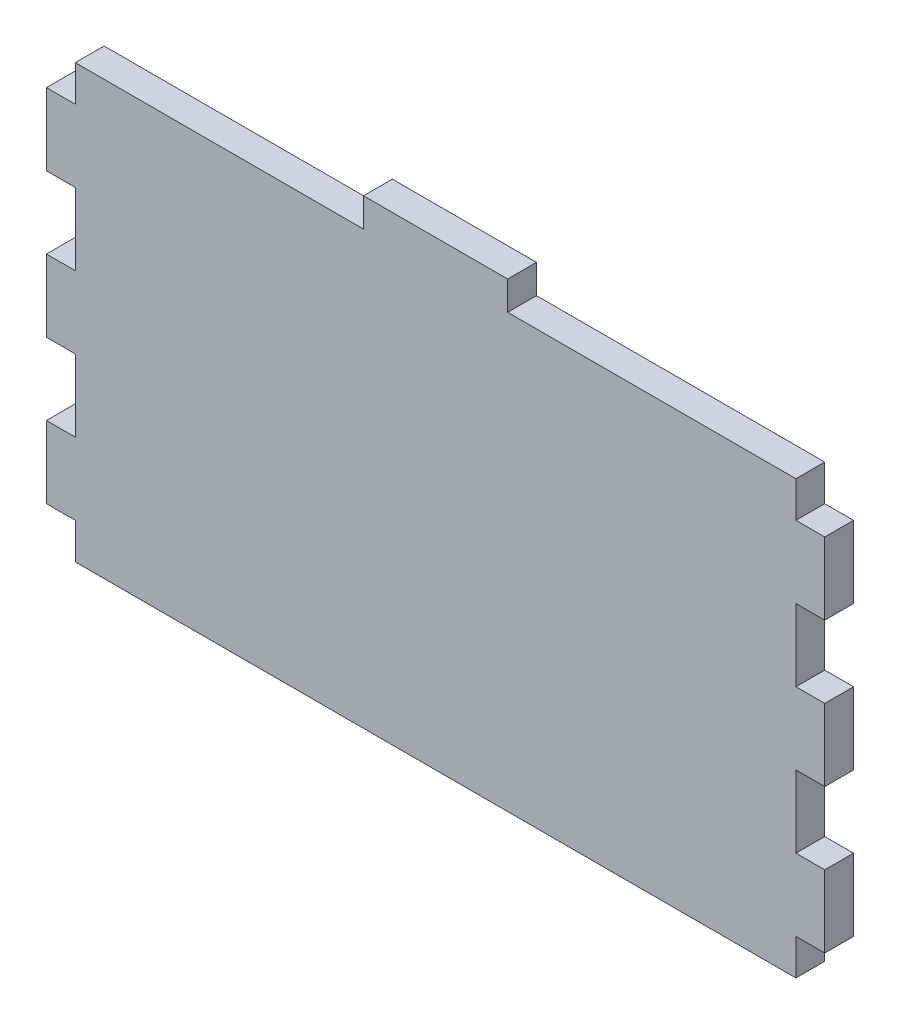
SolidWorks part; units mm, degrees
ref_plane "Front Plane" through (0, 0, 0) normal (0, 0, 1) x (1, 0, 0)
ref_plane "Top Plane" through (0, 0, 0) normal (0, 1, 0) x (1, 0, 0)
ref_plane "Right Plane" through (0, 0, 0) normal (1, 0, 0) x (0, 0, -1)
sketch "Sketch1" plane through (0, 0, 0) normal (0, 0, 1) x (1, 0, 0)
  line L0 (-50, 30) -> (-30, 30)
  line L1 (-50, -30) -> (50, -30)
  line L2 (-50, -30) -> (-50, 30)
  line L3 (-50, 30) -> (50, 30)
  line L4 (50, -30) -> (50, 30)
  line L5 (0, 30) -> (0, -30) construction
  line L6 (-50, 0) -> (50, 0) construction
  line L7 (-30, 30) -> (-10, 30)
  line L8 (-10, 30) -> (10, 30)
  line L9 (10, 30) -> (30, 30)
  line L10 (50, -30) -> (50, -10)
  line L11 (50, -10) -> (50, 10)
  line L12 (-50, -30) -> (-50, -10)
  line L13 (-45, 26) -> (-35, 26)
  line L14 (-45, 26) -> (-45, 34)
  line L15 (-45, 34) -> (-35, 34)
  line L16 (-35, 26) -> (-35, 34)
  line L17 (-40, 34) -> (-40, 26) construction
  line L18 (-45, 30) -> (-35, 30) construction
  line L19 (-25, 26) -> (-15, 26)
  line L20 (-25, 26) -> (-25, 34)
  line L21 (-25, 34) -> (-15, 34)
  line L22 (-15, 26) -> (-15, 34)
  line L23 (-20, 34) -> (-20, 26) construction
  line L24 (-25, 30) -> (-15, 30) construction
  line L25 (-5, 26) -> (5, 26)
  line L26 (-5, 26) -> (-5, 34)
  line L27 (-5, 34) -> (5, 34)
  line L28 (5, 26) -> (5, 34)
  line L29 (0, 34) -> (0, 26) construction
  line L30 (-5, 30) -> (5, 30) construction
  line L31 (15, 26) -> (25, 26)
  line L32 (15, 26) -> (15, 34)
  line L33 (15, 34) -> (25, 34)
  line L34 (25, 26) -> (25, 34)
  line L35 (20, 34) -> (20, 26) construction
  line L36 (15, 30) -> (25, 30) construction
  line L37 (35, 26) -> (45, 26)
  line L38 (35, 26) -> (35, 34)
  line L39 (35, 34) -> (45, 34)
  line L40 (45, 26) -> (45, 34)
  line L41 (40, 34) -> (40, 26) construction
  line L42 (35, 30) -> (45, 30) construction
  line L43 (46, 25) -> (54, 25)
  line L44 (46, 25) -> (46, 15)
  line L45 (46, 15) -> (54, 15)
  line L46 (54, 25) -> (54, 15)
  line L47 (50, 15) -> (50, 25) construction
  line L48 (46, 20) -> (54, 20) construction
  line L49 (46, 5) -> (54, 5)
  line L50 (46, 5) -> (46, -5)
  line L51 (46, -5) -> (54, -5)
  line L52 (54, 5) -> (54, -5)
  line L53 (50, -5) -> (50, 5) construction
  line L54 (46, 0) -> (54, 0) construction
  line L55 (46, -15) -> (54, -15)
  line L56 (46, -15) -> (46, -25)
  line L57 (46, -25) -> (54, -25)
  line L58 (54, -15) -> (54, -25)
  line L59 (50, -25) -> (50, -15) construction
  line L60 (46, -20) -> (54, -20) construction
  line L61 (-50, -10) -> (-50, 10)
  line L63 (-54, 25) -> (-46, 25)
  line L64 (-54, 25) -> (-54, 15)
  line L65 (-54, 15) -> (-46, 15)
  line L66 (-46, 25) -> (-46, 15)
  line L67 (-50, 15) -> (-50, 25) construction
  line L68 (-54, 20) -> (-46, 20) construction
  line L69 (-54, 5) -> (-46, 5)
  line L70 (-54, 5) -> (-54, -5)
  line L71 (-54, -5) -> (-46, -5)
  line L72 (-46, 5) -> (-46, -5)
  line L73 (-50, -5) -> (-50, 5) construction
  line L74 (-54, 0) -> (-46, 0) construction
  line L75 (-54, -15) -> (-46, -15)
  line L76 (-54, -15) -> (-54, -25)
  line L77 (-54, -25) -> (-46, -25)
  line L78 (-46, -15) -> (-46, -25)
  line L79 (-50, -25) -> (-50, -15) construction
  line L80 (-54, -20) -> (-46, -20) construction
  point P0 (0, 0)
  point P4 (-40, 30)
  point P11 (-20, 30)
  point P12 (20, 30)
  point P13 (0, 30)
  point P14 (40, 30)
  point P15 (50, 20)
  point P16 (50, -20)
  point P17 (50, 0)
  point P18 (-40, 30)
  point P22 (-20, 30)
  point P29 (20, 30)
  point P33 (40, 30)
  point P37 (50, 20)
  point P44 (50, -20)
  point P48 (-50, -20)
  point P51 (-50, 0)
  point P52 (-50, 20)
  point P53 (-50, 20)
  point P65 (-50, -20)
  dimension "D1" = 60
  dimension "D2" = 100
  dimension "D3" = 20
  dimension "D4" = 20
  dimension "D5" = 20
  dimension "D6" = 20
  dimension "D7" = 20
  dimension "D8" = 20
  dimension "D9" = 20
  dimension "D10" = 20
  dimension "D11" = 10
  dimension "D12" = 10
  dimension "D13" = 10
  dimension "D14" = 10
  dimension "D15" = 10
  dimension "D16" = 10
  dimension "D17" = 10
  dimension "D18" = 10
  dimension "D19" = 20
  dimension "D20" = 10
  dimension "D21" = 20
  dimension "D22" = 10
  dimension "D23" = 20
  dimension "D24" = 10
  dimension "D25" = 8
  dimension "D26" = 8
  dimension "D27" = 8
  dimension "D28" = 8
  dimension "D29" = 8
  dimension "D30" = 8
  dimension "D31" = 8
  dimension "D32" = 8
  dimension "D33" = 8
  dimension "D34" = 8
  dimension "D35" = 8
  dimension "D36" = 10
  dimension "D37" = 10
  dimension "D38" = 10
  dimension "D39" = 10
  dimension "D40" = 10
  dimension "D41" = 10
  dimension "D42" = 10
  dimension "D43" = 10
  dimension "D44" = 10
  dimension "D45" = 10
  dimension "D46" = 10
extrude "Boss-Extrude1" add sketch "Sketch1" along normal blind 4 contours L75 L78 L77 L2 L1 L4 L57 L56 L55 L10 L51 L50 L49 L11 L45 L44 L43 L3 L40 L37 L38 L34 L31 L32 L28 L25 L26 L22 L19 L20 L0 L16 L13 L14 L63 L66 L65 L61 | L64 L65 L2 L63 | L66 L63 L2 L65 | L70 L71 L61 L69 | L72 L69 L61 L71 | L13 L16 L3 L14 | L78 L75 L12 L77 | L76 L77 L12 L75 | L19 L22 L7 L20 | L25 L28 L8 L26 | L31 L34 L9 L32 | L37 L40 L3 L38 | L46 L43 L4 L45 | L44 L45 L4 L43 | L52 L49 L11 L51 | L50 L51 L11 L49 | L56 L57 L10 L55 | L58 L55 L10 L57
sketch "Sketch2" plane through (0, 0, 4) normal (0, 0, 1) x (1, 0, 0)
  line L0 (-50, 30) -> (50, 30) construction
  line L1 (-10, 26) -> (10, 26)
  line L2 (-10, 26) -> (-10, 34)
  line L3 (-10, 34) -> (10, 34)
  line L4 (10, 26) -> (10, 34)
  line L5 (0, 34) -> (0, 26) construction
  line L6 (-10, 30) -> (10, 30) construction
  point P0 (0, 30)
  dimension "D1" = 8
  dimension "D2" = 20
extrude "Boss-Extrude2" add sketch "Sketch2" against normal blind 4
